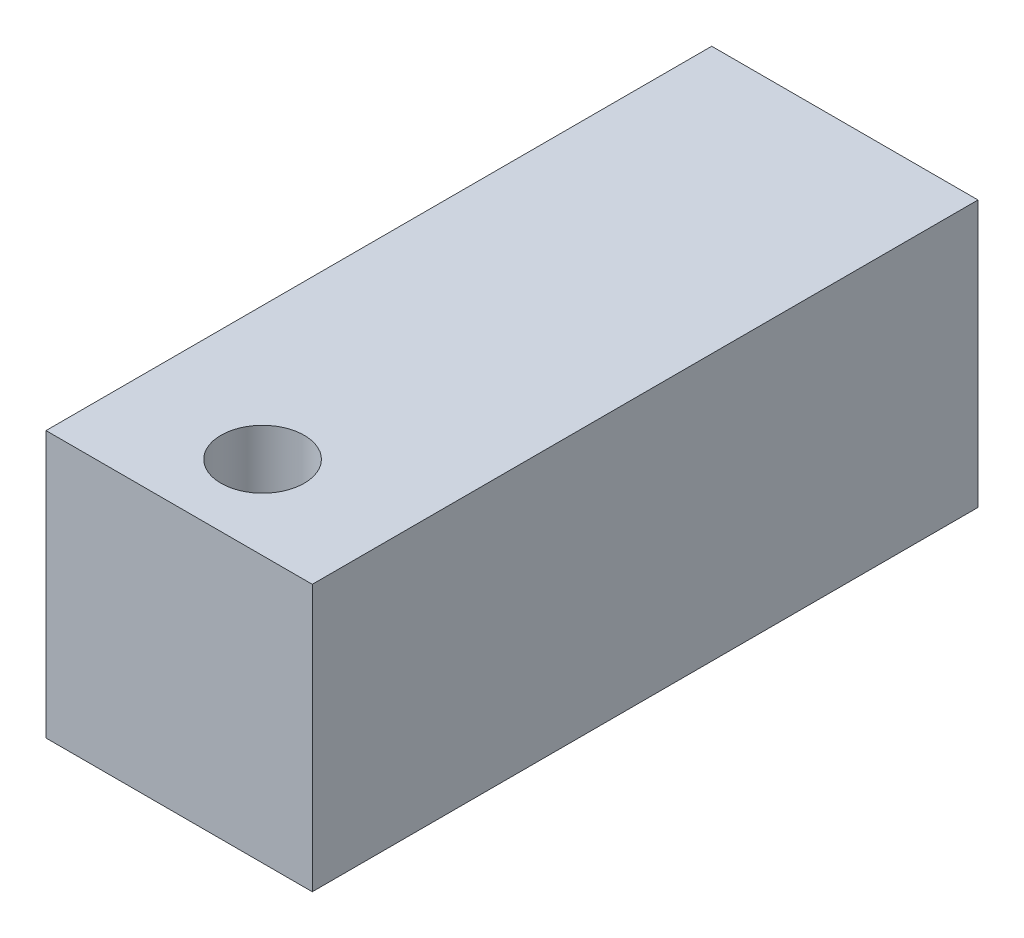
SolidWorks part; units mm, degrees
material "Brass"
ref_plane "Front Plane" through (0, 0, 0) normal (0, 0, 1) x (1, 0, 0)
ref_plane "Top Plane" through (0, 0, 0) normal (0, 1, 0) x (1, 0, 0)
ref_plane "Right Plane" through (0, 0, 0) normal (1, 0, 0) x (0, 0, -1)
sketch "Sketch1" plane through (0, 0, 0) normal (0, 1, 0) x (1, 0, 0)
  line L7 (-1.905, -4.7625) -> (1.905, -4.7625)
  line L8 (-1.905, -4.7625) -> (-1.905, 4.7625)
  line L9 (-1.905, 4.7625) -> (1.905, 4.7625)
  line L10 (1.905, -4.7625) -> (1.905, 4.7625)
  line L11 (-1.905, -4.7625) -> (1.905, 4.7625) construction
  line L12 (-1.905, 4.7625) -> (1.905, -4.7625) construction
  point P0 (0, 0)
  dimension "D1" = 3.81
  dimension "D2" = 0
  dimension "D3" = 9.525
extrude "Boss-Extrude1" add sketch "Sketch1" along normal blind 3.81
hole_wizard "#0-80 Tapped Hole1" positions "Sketch2" profile "Sketch3" tap size "#0-80" standard "ANSI Inch" end condition through all
sketch "Sketch2" plane through (0, 3.81, 0) normal (0, 1, 0) x (1, 0, 0)
  line L0 (-1.905, -4.7625) -> (1.905, -4.7625) construction
  point P5 (0, -3.5687)
  dimension "D1" = 1.1938
cosmetic thread "Hole Thread1"
sketch "Sketch3" plane through (0, 3.81, 3.5687) normal (1, 0, 0) x (0, 0, 1)
  line L0 (0, 0) -> (0, 3.81)
  line L1 (0, 3.81) -> (0.5956, 3.81)
  line L2 (0.5956, 3.81) -> (0.5956, 0)
  line L5 (0.5956, 0) -> (0, 0)
  line L11 (0, -6.35) -> (0, 107.95) construction
  dimension "Thru Tap Drill Dia." = 1.1913
  dimension "Thru Tap Drill Depth" = 3.81
